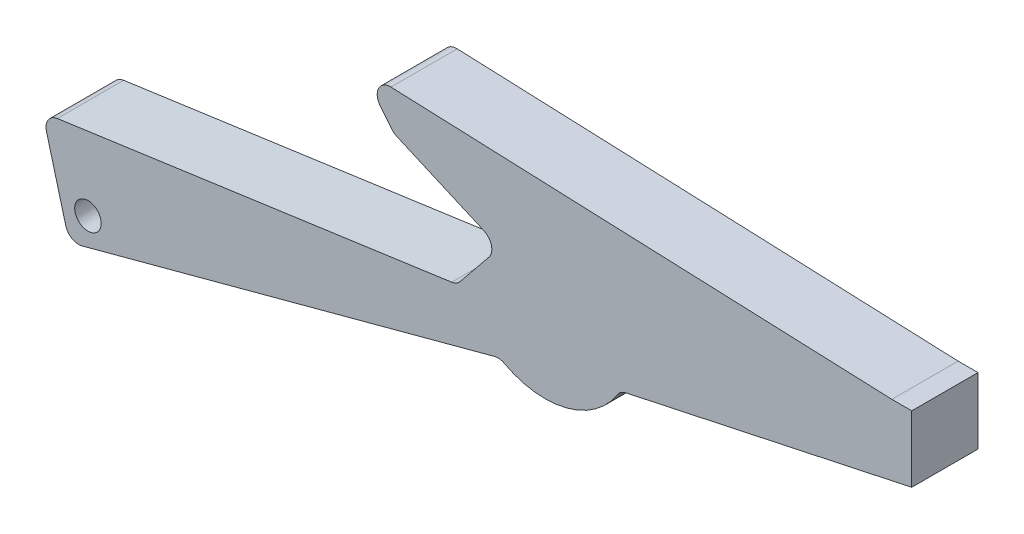
SolidWorks part; units mm, degrees
ref_plane "Front Plane" through (0, 0, 0) normal (1, 0, 0) x (0, 1, 0)
ref_plane "Top Plane" through (0, 0, 0) normal (0, 0, 1) x (0, 1, 0)
ref_plane "Right Plane" through (0, 0, 0) normal (0, 1, 0) x (-1, 0, 0)
sketch "Sketch1" plane through (0, 0, 0) normal (0, 0, 1) x (0, 1, 0)
  line L0 (-4.6879, 27.6813) -> (-139.512, 27.6813) construction
  line L1 (-36.3242, 27.6813) -> (-51.3242, 23.6621)
  line L2 (-51.3242, 23.6621) -> (-33.9075, -41.3379)
  line L3 (-36.3242, 27.6813) -> (-27.5355, -34.8541)
  line L4 (-27.5355, -34.8541) -> (-19.5355, -41.3379)
  line L5 (-19.5355, -41.3379) -> (-12.5454, -25.3379)
  line L6 (-12.5454, -25.3379) -> (-6.5454, -20.5148)
  line L7 (-6.5454, -20.5148) -> (-9.7396, -100.5148)
  line L9 (-19.7396, -100.5148) -> (-19.7396, -103.5148)
  line L10 (-19.7396, -103.5148) -> (-29.1492, -59.5096)
  line L11 (-19.7396, -103.5148) -> (-9.7396, -103.5148)
  line L12 (-9.7396, -103.5148) -> (-9.7396, -100.5148)
  arc A0 (-33.9075, -41.3379) -> (-29.1492, -59.5096) centre (-22.8333, -48.1469) ccw
  dimension "D10" = 13
  dimension "D1" = 15
  dimension "D2" = 15
  dimension "D3" = 90
  dimension "D4" = 65
  dimension "D5" = 83
  dimension "D6" = 8
  dimension "D7" = 16
  dimension "D8" = 6
  dimension "D9" = 80
  dimension "D11" = 45
  dimension "D12" = 3
  dimension "D13" = 10
extrude "Boss-Extrude1" add sketch "Sketch1" along normal blind 10
sketch "Sketch2" plane through (0, 0, 10) normal (0, 0, 1) x (1, 0, 0)
  line L0 (-27.6813, -36.3242) -> (-23.6621, -51.3242) construction
  line L1 (-23.6621, -51.3242) -> (41.3379, -33.9075) construction
  circle A0 centre (-20.8336, -46.4253) radius 2
  dimension "D1" = 4
  dimension "D2" = 4
  dimension "D3" = 4
extrude "Cut-Extrude1" cut sketch "Sketch2" against normal through all
fillet "Fillet1" radius 2 8 edges at (59.5096, -29.1492, 5) (41.3379, -33.9075, 5) (41.3379, -19.5355, 5) (34.8541, -27.5355, 5) (25.3379, -12.5454, 5) (20.5148, -6.5454, 5) (-27.6813, -36.3242, 5) (-23.6621, -51.3242, 5)
